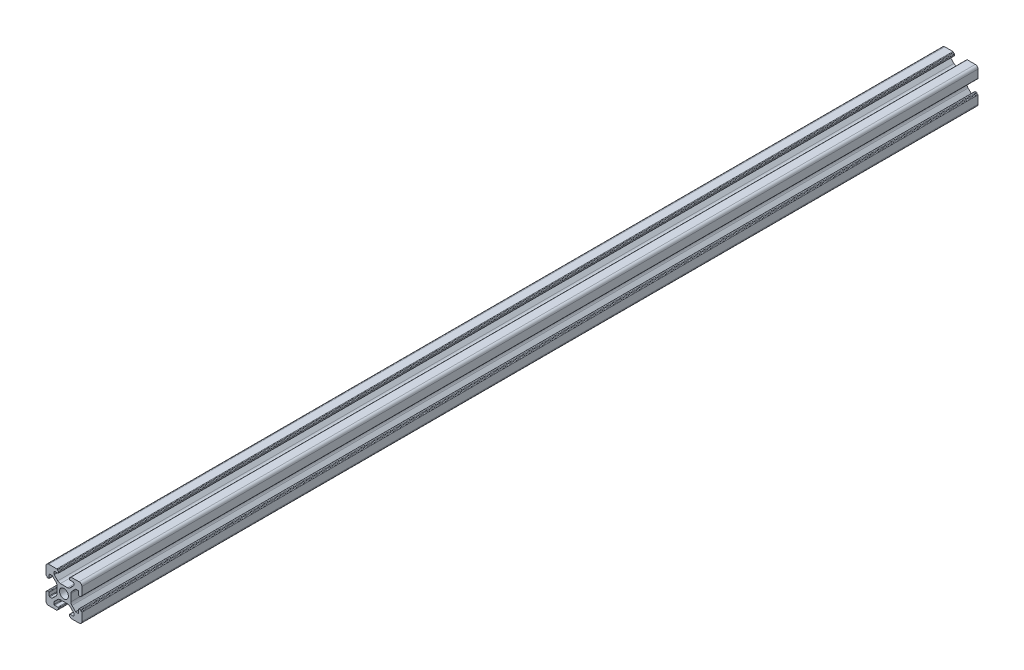
SolidWorks part; units mm, degrees
material "1060 合金"
ref_plane "前视基准面" through (0, 0, 0) normal (0, 0, 1) x (1, 0, 0)
ref_plane "上视基准面" through (0, 0, 0) normal (0, 1, 0) x (1, 0, 0)
ref_plane "右视基准面" through (0, 0, 0) normal (1, 0, 0) x (0, 0, -1)
other "Configuration Table"
sketch "草图1" plane through (0, 0, 0) normal (0, 0, 1) x (1, 0, 0)
  line L0 (-2.5, 0.0329) -> (2.5, 0.0329) construction
  line L1 (10, 8.5329) -> (10, 4.0329)
  line L2 (0, 2.5329) -> (0, -2.4671) construction
  line L3 (10, -8.4671) -> (10, -3.9671)
  line L4 (9.1, -3.0671) -> (8.5, -3.0671)
  line L5 (9.1, 3.1329) -> (8.5, 3.1329)
  line L6 (8.2, 3.4329) -> (8.2, 5.2329)
  line L7 (7.9, 5.5329) -> (6.6849, 5.5329)
  line L8 (6.4728, 5.445) -> (4.4858, 3.458)
  line L9 (3.9, 2.0438) -> (3.9, -1.978)
  line L10 (0, 0.0329) -> (10, 10.0329) construction
  line L11 (8.2, -3.3671) -> (8.2, -5.1671)
  line L12 (7.9, -5.4671) -> (6.6849, -5.4671)
  line L13 (6.4728, -5.3792) -> (4.4858, -3.3922)
  line L14 (5.4121, 6.5057) -> (3.4251, 4.5187)
  line L15 (5.5, 7.9329) -> (5.5, 6.7178)
  line L16 (3.4, 8.2329) -> (5.2, 8.2329)
  line L17 (3.1, 9.1329) -> (3.1, 8.5329)
  line L18 (8.5, 10.0329) -> (4, 10.0329)
  line L19 (-5.4121, 6.5057) -> (-3.4251, 4.5187)
  line L20 (-5.5, 7.9329) -> (-5.5, 6.7178)
  line L21 (-3.4, 8.2329) -> (-5.2, 8.2329)
  line L22 (2.0109, 3.9329) -> (-2.0109, 3.9329)
  line L23 (-3.1, 9.1329) -> (-3.1, 8.5329)
  line L24 (-8.5, 10.0329) -> (-4, 10.0329)
  line L25 (-10, 10.0329) -> (0, 0.0329) construction
  line L26 (-10, 8.5329) -> (-10, 4.0329)
  line L27 (-9.1, 3.1329) -> (-8.5, 3.1329)
  line L28 (-3.9, -1.978) -> (-3.9, 2.0438)
  line L29 (-8.2, 3.4329) -> (-8.2, 5.2329)
  line L30 (-7.9, 5.5329) -> (-6.6849, 5.5329)
  line L31 (-6.4728, 5.445) -> (-4.4858, 3.458)
  line L32 (-10, -8.4671) -> (-10, -3.9671)
  line L33 (-9.1, -3.0671) -> (-8.5, -3.0671)
  line L34 (-8.2, -3.3671) -> (-8.2, -5.1671)
  line L35 (-7.9, -5.4671) -> (-6.6849, -5.4671)
  line L36 (-6.4728, -5.3792) -> (-4.4858, -3.3922)
  line L37 (5.4121, -6.4399) -> (3.4251, -4.4529)
  line L38 (5.5, -7.8671) -> (5.5, -6.652)
  line L39 (3.4, -8.1671) -> (5.2, -8.1671)
  line L40 (-2.0109, -3.8671) -> (2.0109, -3.8671)
  line L41 (-5.4121, -6.4399) -> (-3.4251, -4.4529)
  line L42 (-5.5, -7.8671) -> (-5.5, -6.652)
  line L43 (-3.4, -8.1671) -> (-5.2, -8.1671)
  line L44 (-3.1, -9.0671) -> (-3.1, -8.4671)
  line L45 (3.1, -9.0671) -> (3.1, -8.4671)
  line L46 (8.5, -9.9671) -> (4, -9.9671)
  line L47 (-8.5, -9.9671) -> (-4, -9.9671)
  circle A0 centre (0, 0.0329) radius 2.5
  arc A1 (4.4858, 3.458) -> (3.9, 2.0438) centre (5.9, 2.0438) ccw
  arc A2 (10, 4.0329) -> (9.7, 3.7329) centre (9.7, 4.0329) cw
  arc A3 (9.1, 3.1329) -> (9.4, 3.4329) centre (9.1, 3.4329) ccw
  arc A4 (8.5, 3.1329) -> (8.2, 3.4329) centre (8.5, 3.4329) cw
  arc A5 (8.2, 5.2329) -> (7.9, 5.5329) centre (7.9, 5.2329) ccw
  arc A6 (6.6849, 5.5329) -> (6.4728, 5.445) centre (6.6849, 5.2329) ccw
  arc A7 (9.4, 3.4329) -> (9.7, 3.7329) centre (9.7, 3.4329) cw
  arc A8 (10, -3.9671) -> (9.7, -3.6671) centre (9.7, -3.9671) ccw
  arc A9 (9.4, -3.3671) -> (9.7, -3.6671) centre (9.7, -3.3671) ccw
  arc A10 (9.1, -3.0671) -> (9.4, -3.3671) centre (9.1, -3.3671) cw
  arc A11 (8.5, -3.0671) -> (8.2, -3.3671) centre (8.5, -3.3671) ccw
  arc A12 (8.2, -5.1671) -> (7.9, -5.4671) centre (7.9, -5.1671) cw
  arc A13 (6.6849, -5.4671) -> (6.4728, -5.3792) centre (6.6849, -5.1671) cw
  arc A14 (4.4858, -3.3922) -> (3.9, -1.978) centre (5.9, -1.978) cw
  arc A15 (3.4, 9.4329) -> (3.7, 9.7329) centre (3.4, 9.7329) ccw
  arc A16 (5.5, 6.7178) -> (5.4121, 6.5057) centre (5.2, 6.7178) cw
  arc A17 (5.2, 8.2329) -> (5.5, 7.9329) centre (5.2, 7.9329) cw
  arc A18 (3.1, 8.5329) -> (3.4, 8.2329) centre (3.4, 8.5329) ccw
  arc A19 (3.1, 9.1329) -> (3.4, 9.4329) centre (3.4, 9.1329) cw
  arc A20 (4, 10.0329) -> (3.7, 9.7329) centre (4, 9.7329) ccw
  arc A21 (-3.4251, 4.5187) -> (-2.0109, 3.9329) centre (-2.0109, 5.9329) ccw
  arc A22 (-5.5, 6.7178) -> (-5.4121, 6.5057) centre (-5.2, 6.7178) ccw
  arc A23 (-5.2, 8.2329) -> (-5.5, 7.9329) centre (-5.2, 7.9329) ccw
  arc A24 (-3.1, 8.5329) -> (-3.4, 8.2329) centre (-3.4, 8.5329) cw
  arc A25 (-3.1, 9.1329) -> (-3.4, 9.4329) centre (-3.4, 9.1329) ccw
  arc A26 (-3.4, 9.4329) -> (-3.7, 9.7329) centre (-3.4, 9.7329) cw
  arc A27 (-4, 10.0329) -> (-3.7, 9.7329) centre (-4, 9.7329) cw
  arc A28 (3.4251, 4.5187) -> (2.0109, 3.9329) centre (2.0109, 5.9329) cw
  arc A29 (-4.4858, -3.3922) -> (-3.9, -1.978) centre (-5.9, -1.978) ccw
  arc A30 (-10, 4.0329) -> (-9.7, 3.7329) centre (-9.7, 4.0329) ccw
  arc A31 (-9.4, 3.4329) -> (-9.7, 3.7329) centre (-9.7, 3.4329) ccw
  arc A32 (-9.1, 3.1329) -> (-9.4, 3.4329) centre (-9.1, 3.4329) cw
  arc A33 (-8.5, 3.1329) -> (-8.2, 3.4329) centre (-8.5, 3.4329) ccw
  arc A34 (-8.2, 5.2329) -> (-7.9, 5.5329) centre (-7.9, 5.2329) cw
  arc A35 (-6.6849, 5.5329) -> (-6.4728, 5.445) centre (-6.6849, 5.2329) cw
  arc A36 (-4.4858, 3.458) -> (-3.9, 2.0438) centre (-5.9, 2.0438) cw
  arc A37 (-10, -3.9671) -> (-9.7, -3.6671) centre (-9.7, -3.9671) cw
  arc A38 (-9.1, -3.0671) -> (-9.4, -3.3671) centre (-9.1, -3.3671) ccw
  arc A39 (-8.5, -3.0671) -> (-8.2, -3.3671) centre (-8.5, -3.3671) cw
  arc A40 (-8.2, -5.1671) -> (-7.9, -5.4671) centre (-7.9, -5.1671) ccw
  arc A41 (-6.6849, -5.4671) -> (-6.4728, -5.3792) centre (-6.6849, -5.1671) ccw
  arc A42 (-9.4, -3.3671) -> (-9.7, -3.6671) centre (-9.7, -3.3671) cw
  arc A43 (3.4251, -4.4529) -> (2.0109, -3.8671) centre (2.0109, -5.8671) ccw
  arc A44 (5.5, -6.652) -> (5.4121, -6.4399) centre (5.2, -6.652) ccw
  arc A45 (5.2, -8.1671) -> (5.5, -7.8671) centre (5.2, -7.8671) ccw
  arc A46 (3.1, -8.4671) -> (3.4, -8.1671) centre (3.4, -8.4671) cw
  arc A47 (3.1, -9.0671) -> (3.4, -9.3671) centre (3.4, -9.0671) ccw
  arc A48 (3.4, -9.3671) -> (3.7, -9.6671) centre (3.4, -9.6671) cw
  arc A49 (4, -9.9671) -> (3.7, -9.6671) centre (4, -9.6671) cw
  arc A50 (-3.4, -9.3671) -> (-3.7, -9.6671) centre (-3.4, -9.6671) ccw
  arc A51 (-5.5, -6.652) -> (-5.4121, -6.4399) centre (-5.2, -6.652) cw
  arc A52 (-5.2, -8.1671) -> (-5.5, -7.8671) centre (-5.2, -7.8671) cw
  arc A53 (-3.1, -8.4671) -> (-3.4, -8.1671) centre (-3.4, -8.4671) ccw
  arc A54 (-3.1, -9.0671) -> (-3.4, -9.3671) centre (-3.4, -9.0671) cw
  arc A55 (-4, -9.9671) -> (-3.7, -9.6671) centre (-4, -9.6671) ccw
  arc A56 (-3.4251, -4.4529) -> (-2.0109, -3.8671) centre (-2.0109, -5.8671) cw
  arc A57 (-10, -8.4671) -> (-8.5, -9.9671) centre (-8.5, -8.4671) ccw
  arc A58 (8.5, -9.9671) -> (10, -8.4671) centre (8.5, -8.4671) ccw
  arc A59 (10, 8.5329) -> (8.5, 10.0329) centre (8.5, 8.5329) ccw
  arc A60 (-10, 8.5329) -> (-8.5, 10.0329) centre (-8.5, 8.5329) cw
  point P47 (3.9, 0.0329)
  point P86 (0, 3.9329)
  point P164 (-3.9, 0.0329)
  point P165 (0, -3.8671)
  dimension "D1" = 5
extrude "凸台-拉伸1" add sketch "草图1" along normal blind 500
